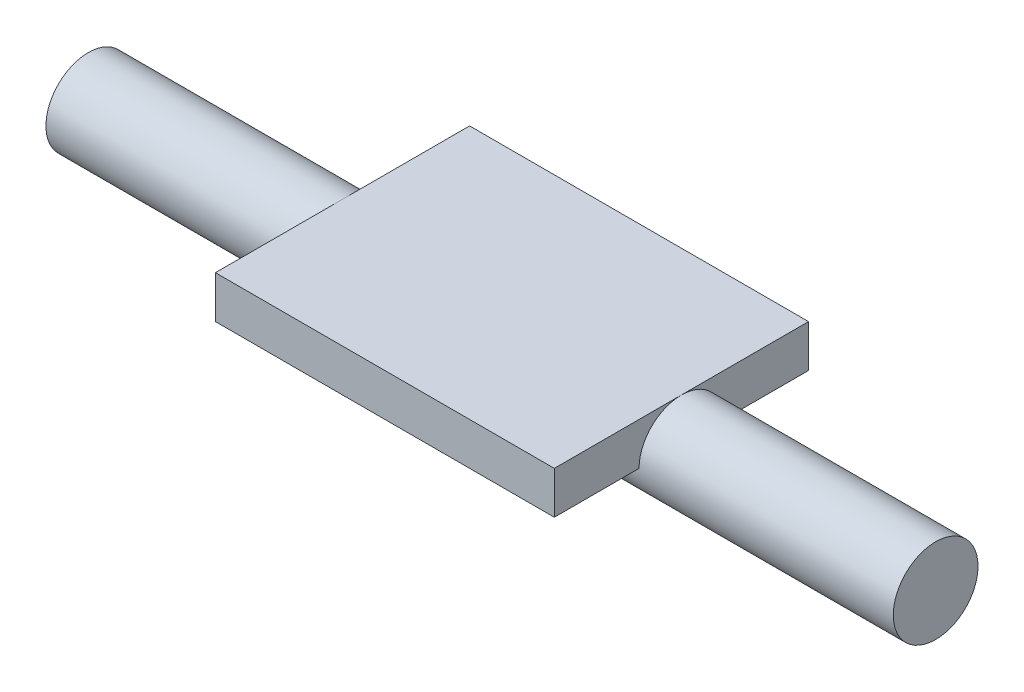
SolidWorks part; units mm, degrees
ref_plane "前视基准面" through (0, 0, 0) normal (0, 0, 1) x (1, 0, 0)
ref_plane "上视基准面" through (0, 0, 0) normal (0, 1, 0) x (1, 0, 0)
ref_plane "右视基准面" through (0, 0, 0) normal (1, 0, 0) x (0, 0, -1)
sketch "草图2" plane through (0, 0, 0) normal (1, 0, 0) x (0, 0, -1)
  circle A0 centre (0, 0) radius 2.5
extrude "凸台-拉伸1" add sketch "草图2" against normal blind 50
sketch "草图4" plane through (0, 0, 0) normal (1, 0, 0) x (0, 0, -1)
  line L0 (-2.5, 0) -> (2.5, 0)
  circle A0 centre (0, 0) radius 2.5 construction
  arc A1 (-2.5, 0) -> (2.5, 0) centre (0, 0) cw
extrude "切除-拉伸1" cut sketch "草图4" against normal blind 20 from offset 15 offset against normal yes
sketch "草图5" plane through (0, 0, 0) normal (0, 1, 0) x (1, 0, 0)
  line L1 (-35, -7.5) -> (-15, -7.5)
  line L2 (-35, -7.5) -> (-35, 7.5)
  line L3 (-35, 7.5) -> (-15, 7.5)
  line L4 (-15, -7.5) -> (-15, 7.5)
  line L5 (-35, -7.5) -> (-15, 7.5) construction
  line L6 (-35, 7.5) -> (-15, -7.5) construction
  point P0 (-25, 0)
extrude "凸台-拉伸2" add sketch "草图5" along normal blind 2.5
